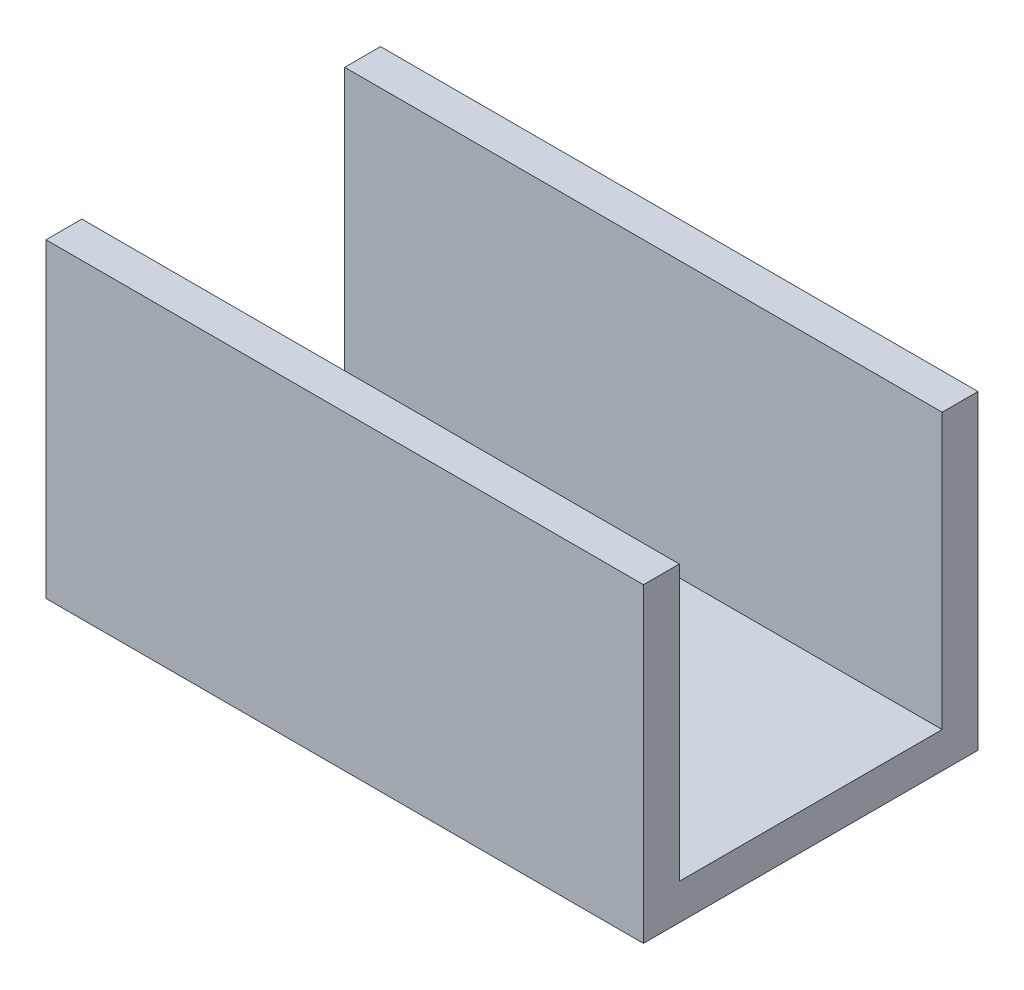
SolidWorks part; units mm, degrees
ref_plane "Front Plane" through (0, 0, 0) normal (0, 0, 1) x (1, 0, 0)
ref_plane "Top Plane" through (0, 0, 0) normal (0, 1, 0) x (1, 0, 0)
ref_plane "Right Plane" through (0, 0, 0) normal (1, 0, 0) x (0, 0, -1)
sketch "Sketch1" plane through (0, 0, 0) normal (0, 1, 0) x (1, 0, 0)
  line L1 (0, 0) -> (100, 0)
  line L2 (0, 0) -> (0, 56)
  line L3 (0, 56) -> (100, 56)
  line L4 (100, 0) -> (100, 56)
  dimension "D1" = 100
  dimension "D2" = 56
extrude "Boss-Extrude1" add sketch "Sketch1" along normal blind 52 contours L4 L3 L2 L1
ref_point "Point1"
ref_point "Point2"
sketch "Sketch4" plane through (0, 0, 0) normal (-1, 0, 0) x (0, 0, 1)
  line L0 (0, 0) -> (-56, 0) construction
  line L1 (-50, 56) -> (-6, 56)
  line L2 (-50, 56) -> (-50, 6)
  line L3 (-50, 6) -> (-6, 6)
  line L4 (-6, 56) -> (-6, 6)
  line L5 (-50, 56) -> (-6, 6) construction
  line L6 (-50, 6) -> (-6, 56) construction
  point P6 (-28, 31)
  dimension "D1" = 44
  dimension "D2" = 50
  dimension "D3" = 6
extrude "Cut-Extrude2" cut sketch "Sketch4" against normal through all
